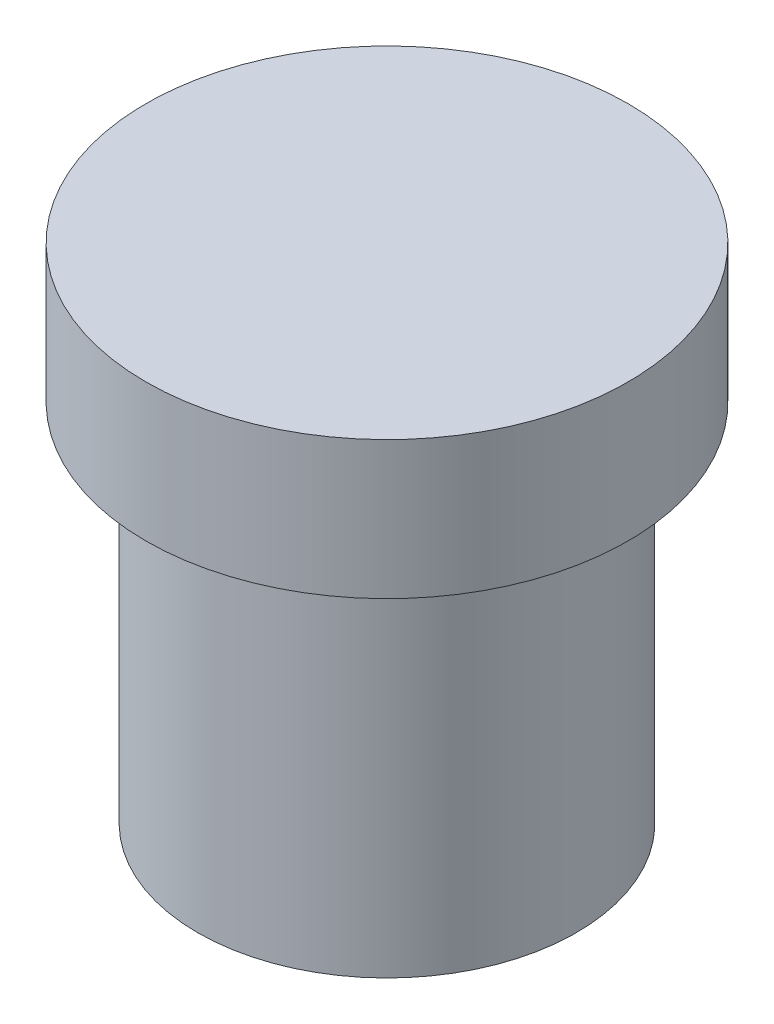
SolidWorks part; units mm, degrees
ref_plane "Front Plane" through (0, 0, 0) normal (0, 0, 1) x (1, 0, 0)
ref_plane "Top Plane" through (0, 0, 0) normal (0, 1, 0) x (1, 0, 0)
ref_plane "Right Plane" through (0, 0, 0) normal (1, 0, 0) x (0, 0, -1)
sketch "Sketch1" plane through (0, 0, 0) normal (0, 1, 0) x (1, 0, 0)
  circle A0 centre (0, 0) radius 5
  dimension "D1" = 10
extrude "Boss-Extrude1" add sketch "Sketch1" along normal blind 10 contours A0
sketch "Sketch2" plane through (0, 10, 0) normal (0, 1, 0) x (1, 0, 0)
  circle A0 centre (0, 0) radius 27.5
  dimension "D1" = 55
extrude "Boss-Extrude2" add sketch "Sketch2" along normal blind 53
sketch "Sketch3" plane through (0, 63, 0) normal (0, 1, 0) x (1, 0, 0)
  circle A0 centre (0, 0) radius 35
  dimension "D1" = 70
extrude "Boss-Extrude3" add sketch "Sketch3" along normal blind 20
